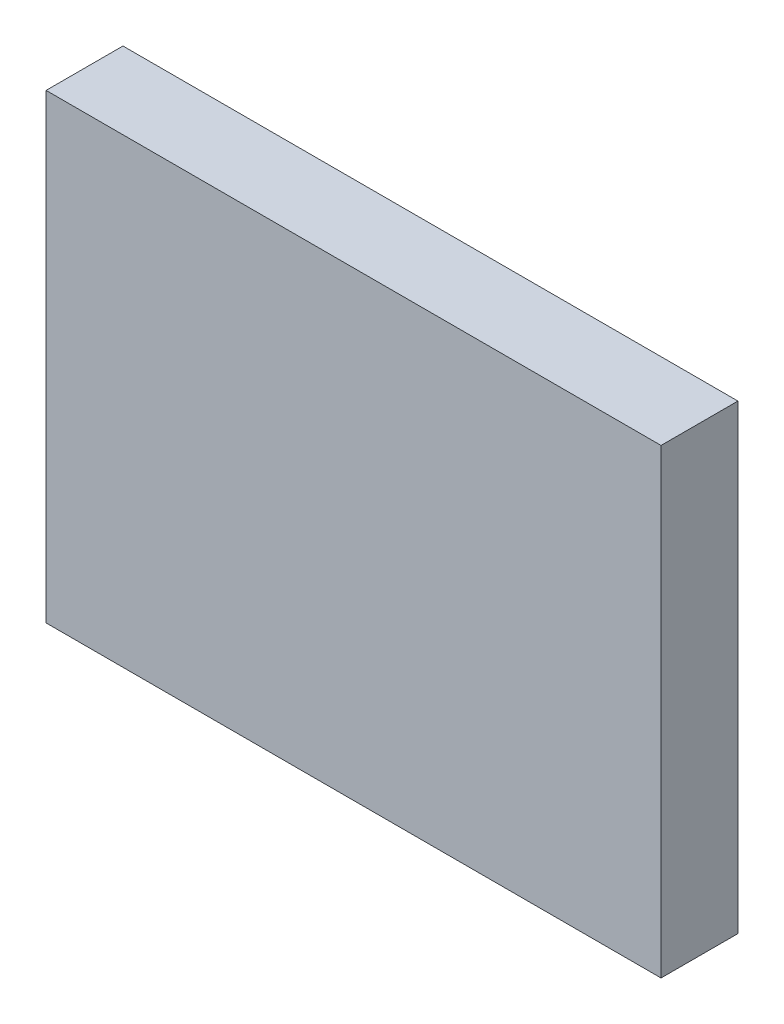
SolidWorks part; units mm, degrees
ref_plane "Plan de face" through (0, 0, 0) normal (0, 0, 1) x (1, 0, 0)
ref_plane "Plan de dessus" through (0, 0, 0) normal (0, 1, 0) x (1, 0, 0)
ref_plane "Plan de droite" through (0, 0, 0) normal (1, 0, 0) x (0, 0, -1)
sketch "Esquisse1" plane through (0, 0, 0) normal (0, 0, 1) x (1, 0, 0)
  line L1 (0, 0) -> (80, 0)
  line L2 (0, 0) -> (0, -60)
  line L3 (0, -60) -> (80, -60)
  line L4 (80, 0) -> (80, -60)
  dimension "D1" = 60
  dimension "D2" = 80
extrude "Boss.-Extru.1" add sketch "Esquisse1" along normal blind 10
